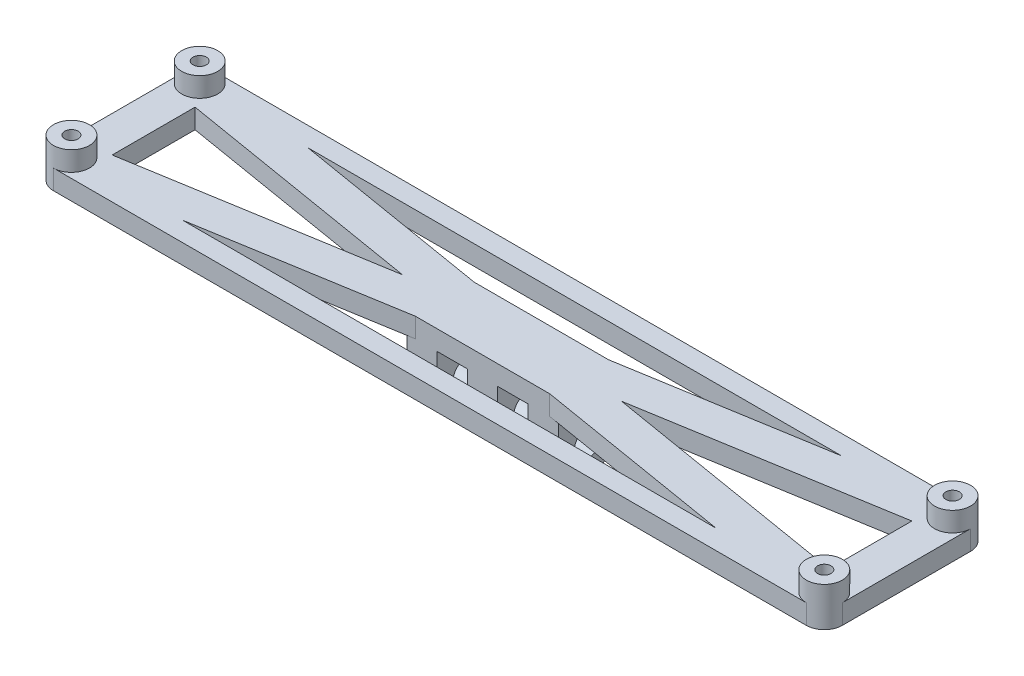
SolidWorks part; units mm, degrees
material "CARBON FIBER TEST"
ref_plane "Front Plane" through (0, 0, 0) normal (0, 0, 1) x (1, 0, 0)
ref_plane "Top Plane" through (0, 0, 0) normal (0, 1, 0) x (1, 0, 0)
ref_plane "Right Plane" through (0, 0, 0) normal (1, 0, 0) x (0, 0, -1)
sketch "Sketch1" plane through (0, 0, 0) normal (0, 1, 0) x (1, 0, 0)
  line L1 (-38.36, 6.39) -> (-27.1925, 6.39) construction
  line L2 (-38.36, 6.39) -> (-38.36, -6.39) construction
  line L3 (-38.36, -6.39) -> (-36.525, -6.39) construction
  line L4 (38.36, 4.555) -> (38.36, 4.5297) construction
  line L7 (-38.0585, 8.2001) -> (-3.0899, 2.375) construction
  line L8 (-38.6615, 4.5799) -> (-11.1675, 0) construction
  line L10 (-38.6615, -4.5799) -> (-11.1675, 0) construction
  line L12 (11.1675, 0) -> (36.525, -4.224) construction
  line L13 (-3.0899, 2.375) -> (3.0899, 2.375) construction
  line L15 (-3.0899, -2.375) -> (3.0899, -2.375) construction
  line L17 (-38.36, 6.39) -> (-38.36, -6.39) construction
  line L18 (3.0899, 2.375) -> (16.1767, 4.555) construction
  line L19 (11.1675, 0) -> (36.525, 4.224) construction
  line L24 (3.0899, -2.375) -> (16.1767, -4.555) construction
  line L25 (-36.525, 6.39) -> (-36.525, -4.555) construction
  line L26 (-40.195, 6.39) -> (-40.195, -6.39) construction
  line L30 (-38.36, -6.39) -> (-36.525, -6.39) construction
  line L31 (-38.36, -4.555) -> (-36.525, -4.555) construction
  line L32 (-38.36, -8.225) -> (38.36, -8.225) construction
  line L33 (38.36, 4.555) -> (38.36, 4.5297) construction
  line L34 (40.195, 6.39) -> (40.195, -6.39) construction
  line L35 (36.525, 4.224) -> (36.525, -4.555) construction
  line L37 (16.1767, 4.555) -> (-38.36, 4.555) construction
  line L38 (38.36, 8.225) -> (-38.36, 8.225) construction
  line L39 (38.36, -4.5297) -> (38.6615, -4.5799) construction
  line L41 (-27.1925, 6.39) -> (-38.36, 6.39) construction
  line L42 (38.36, -4.5297) -> (38.36, -6.39) construction
  line L43 (38.36, -4.5297) -> (38.36, -6.39) construction
  line L44 (-16.1767, -4.555) -> (-3.0899, -2.375) construction
  line L45 (-16.1767, -4.555) -> (16.1767, -4.555) construction
  arc A0 (-38.0585, 8.2001) -> (-38.6615, 4.5799) centre (-38.36, 6.39) ccw construction
  arc A1 (38.0585, -8.2001) -> (38.6615, -4.5799) centre (38.36, -6.39) ccw construction
  arc A2 (-38.6615, -4.5799) -> (-38.0585, -8.2001) centre (-38.36, -6.39) ccw construction
  arc A3 (40.195, 6.39) -> (38.0585, 8.2001) centre (38.36, 6.39) ccw construction
  arc A4 (-36.525, 6.39) -> (-40.195, 6.39) centre (-38.36, 6.39) ccw construction
  arc A5 (-40.195, -6.39) -> (-36.525, -6.39) centre (-38.36, -6.39) ccw construction
  arc A8 (-38.36, -4.555) -> (-38.36, -8.225) centre (-38.36, -6.39) ccw construction
  arc A9 (38.36, -8.225) -> (38.36, -4.555) centre (38.36, -6.39) ccw construction
  arc A10 (40.195, 6.39) -> (38.0585, 8.2001) centre (38.36, 6.39) ccw construction
  arc A11 (38.0585, -8.2001) -> (40.195, -6.39) centre (38.36, -6.39) ccw construction
  arc A13 (-38.36, 8.225) -> (-38.36, 4.555) centre (-38.36, 6.39) ccw construction
  arc A14 (40.195, 6.39) -> (38.36, 8.225) centre (38.36, 6.39) ccw construction
  circle A15 centre (-38.36, 6.39) radius 1.2491
  point P0 (0, 0)
  point P6 (0, 0)
  point P11 (0, 0)
  point P16 (0, 0)
  point P17 (-38.36, 0)
  point P26 (0, 6.39)
  point P35 (0, -6.39)
  point P43 (38.36, 0)
  dimension "D2" = 12.78
sketch "Sketch2" plane through (0, 0, 0) normal (0, 1, 0) x (1, 0, 0)
  line L0 (-38.36, 6.39) -> (38.36, -6.39) construction
  line L1 (38.36, -6.39) -> (-38.36, -6.39) construction
  line L2 (38.36, -6.39) -> (38.36, 6.39) construction
  line L3 (38.36, 6.39) -> (-38.36, 6.39) construction
  line L4 (-38.36, -6.39) -> (-38.36, 6.39) construction
  line L5 (38.36, -6.39) -> (-38.36, 6.39) construction
  line L6 (38.36, 6.39) -> (-38.36, -6.39) construction
  line L7 (-38.0585, 8.2001) -> (38.6615, -4.5799) construction
  line L8 (-38.6615, 4.5799) -> (38.0585, -8.2001) construction
  line L9 (-38.36, -6.39) -> (38.36, 6.39) construction
  line L10 (-38.6615, -4.5799) -> (38.0585, 8.2001) construction
  line L11 (-38.0585, -8.2001) -> (38.6615, 4.5799) construction
  line L12 (-38.36, 6.39) -> (-38.36, -6.39) construction
  line L19 (-36.525, 6.39) -> (-36.525, -6.39) construction
  line L20 (-40.195, 6.39) -> (-40.195, -6.39) construction
  line L21 (38.36, 6.39) -> (38.36, -6.39) construction
  line L22 (40.195, 6.39) -> (40.195, -6.39) construction
  line L23 (36.525, 6.39) -> (36.525, -6.39) construction
  line L24 (-38.36, 6.39) -> (38.36, 6.39) construction
  line L25 (-38.36, 8.225) -> (38.36, 8.225) construction
  line L26 (-38.36, 4.555) -> (38.36, 4.555) construction
  line L27 (-38.36, -6.39) -> (38.36, -6.39) construction
  line L28 (-38.36, -4.555) -> (38.36, -4.555) construction
  line L29 (-38.36, -8.225) -> (38.36, -8.225) construction
  line L31 (-7.715, 3) -> (7.715, 3)
  line L32 (-7.715, 3) -> (-7.715, -3)
  line L33 (-7.715, -3) -> (7.715, -3)
  line L34 (7.715, 3) -> (7.715, -3)
  line L35 (-7.715, 3) -> (7.715, -3) construction
  line L36 (-7.715, -3) -> (7.715, 3) construction
  arc A0 (-38.0585, 8.2001) -> (-38.6615, 4.5799) centre (-38.36, 6.39) ccw construction
  arc A1 (38.0585, -8.2001) -> (38.6615, -4.5799) centre (38.36, -6.39) ccw construction
  arc A2 (-38.6615, -4.5799) -> (-38.0585, -8.2001) centre (-38.36, -6.39) ccw construction
  arc A3 (38.6615, 4.5799) -> (38.0585, 8.2001) centre (38.36, 6.39) ccw construction
  arc A4 (-36.525, 6.39) -> (-40.195, 6.39) centre (-38.36, 6.39) ccw construction
  arc A5 (-40.195, -6.39) -> (-36.525, -6.39) centre (-38.36, -6.39) ccw construction
  arc A6 (40.195, 6.39) -> (36.525, 6.39) centre (38.36, 6.39) ccw construction
  arc A7 (36.525, -6.39) -> (40.195, -6.39) centre (38.36, -6.39) ccw construction
  arc A8 (-38.36, 8.225) -> (-38.36, 4.555) centre (-38.36, 6.39) ccw construction
  arc A9 (38.36, 4.555) -> (38.36, 8.225) centre (38.36, 6.39) ccw construction
  arc A10 (-38.36, -4.555) -> (-38.36, -8.225) centre (-38.36, -6.39) ccw construction
  arc A11 (38.36, -8.225) -> (38.36, -4.555) centre (38.36, -6.39) ccw construction
  point P0 (0, 0)
  point P7 (0, 0)
  point P12 (0, 0)
  point P17 (0, 0)
  point P18 (0, 0)
  point P25 (-38.36, 0)
  point P30 (38.36, 0)
  point P39 (0, 6.39)
  point P46 (0, -6.39)
  dimension "D1" = 15.43
  dimension "D2" = 6
sketch "Sketch3" plane through (0, 0, 0) normal (0, 1, 0) x (1, 0, 0)
  line L2 (6.8419, -3) -> (27.1925, -6.39)
  line L5 (-27.1925, 6.39) -> (-6.8419, 3)
  line L6 (0, 0) -> (-4.9915, 0) construction
  line L7 (-36.525, 4.224) -> (-36.525, -4.224)
  line L8 (-36.525, 6.39) -> (-36.525, -4.555) construction
  line L9 (-38.6615, 4.5799) -> (-11.1675, 0) construction
  line L10 (-38.6615, -4.5799) -> (-11.1675, 0) construction
  line L11 (-36.525, -4.224) -> (-11.1675, 0)
  line L12 (-11.1675, 0) -> (-36.525, 4.224)
  line L13 (6.8419, 3) -> (27.1925, 6.39)
  line L14 (38.36, 6.39) -> (-38.36, 6.39) construction
  line L15 (-38.6615, -4.5799) -> (38.0585, 8.2001) construction
  line L16 (27.1925, 6.39) -> (-27.1925, 6.39)
  line L17 (0, 0) -> (32.5589, 0) construction
  line L18 (-6.8419, -3) -> (6.8419, -3)
  line L19 (0, 0) -> (0, -14.67) construction
  line L20 (-27.1925, -6.39) -> (-6.8419, -3)
  line L21 (27.1925, -6.39) -> (-27.1925, -6.39)
  line L22 (36.525, -4.224) -> (11.1675, 0)
  line L23 (36.525, 4.224) -> (36.525, -4.224)
  line L24 (11.1675, 0) -> (36.525, 4.224)
  line L25 (-6.8419, 3) -> (6.8419, 3)
  line L26 (38.36, -8.37) -> (-38.36, -8.37)
  line L27 (40.195, -6.535) -> (40.195, 6.535)
  line L28 (38.36, 8.37) -> (-38.36, 8.37)
  line L29 (-40.195, -6.535) -> (-40.195, 6.535)
  line L30 (40.195, -8.37) -> (-40.195, 8.37) construction
  line L31 (40.195, 8.37) -> (-40.195, -8.37) construction
  arc A0 (-40.195, 6.535) -> (-38.36, 8.37) centre (-38.36, 6.535) cw
  arc A1 (38.36, -8.37) -> (40.195, -6.535) centre (38.36, -6.535) ccw
  arc A2 (40.195, 6.535) -> (38.36, 8.37) centre (38.36, 6.535) ccw
  arc A3 (-38.36, -8.37) -> (-40.195, -6.535) centre (-38.36, -6.535) cw
  dimension "D3" = 1.835
  dimension "D4" = 1.835
  dimension "D1" = 16.74
  dimension "D2" = 80.39
  dimension "D5" = 6
extrude "Boss-Extrude2" add sketch "Sketch3" along normal blind 2
ref_plane "Plane2" through (7.715, 0, 0) normal (-1, 0, 0) x (0, 0, 1)
sketch "Sketch7" plane through (7.715, 0, 0) normal (-1, 0, 0) x (0, 0, 1)
  line L0 (-3, 0) -> (3, 0) construction
  line L4 (-3, 0) -> (3, 0)
  line L5 (-3, -3.4) -> (-3, 0)
  line L6 (3, -3.4) -> (3, 0)
  circle A2 centre (0, -3.4) radius 1.375
  arc A3 (-3, -3.4) -> (3, -3.4) centre (0, -3.4) ccw
  dimension "D1" = 2.75
  dimension "D3" = 3.4
  dimension "D2" = 6
extrude "Boss-Extrude4" add sketch "Sketch7" along normal blind 3.086
pattern_linear "LPattern1" count 3 spacing 6.172 along (-1, 0, 0) of "Boss-Extrude4"
sketch "Sketch8" plane through (0, 2, 0) normal (0, 1, 0) x (1, 0, 0)
  line L0 (-40.195, 4.7227) -> (-38.36, 4.7227) construction
  line L1 (-40.195, 6.535) -> (-40.195, -6.535) construction
  line L2 (-36.6331, 8.37) -> (-36.6331, 6.535) construction
  line L3 (38.36, 8.37) -> (-38.36, 8.37) construction
  line L4 (0, 0) -> (0, -4.7834) construction
  circle A0 centre (-38.36, 6.535) radius 0.985 construction
  circle A1 centre (38.36, 6.535) radius 0.985 construction
  circle A2 centre (-38.36, 6.535) radius 1.835
  arc A4 (-38.36, 8.37) -> (-40.195, 6.535) centre (-38.36, 6.535) ccw construction
  point P4 (-37.375, 6.535)
  point P5 (-39.345, 6.535)
  point P6 (37.375, 6.535)
  point P7 (39.345, 6.535)
  dimension "D1" = 74.75
  dimension "D2" = 78.69
extrude "Boss-Extrude5" add sketch "Sketch8" along normal blind 2
sketch "Sketch9" plane through (0, 4, 0) normal (0, 1, 0) x (1, 0, 0)
  circle A0 centre (-38.36, 6.535) radius 0.685
  point P3 (-37.675, 6.535)
  dimension "D1" = 0.3
extrude "Cut-Extrude1" cut sketch "Sketch9" against normal through all
mirror "Mirror1" about plane through (0, 0, 0) normal (1, 0, 0) of "Boss-Extrude5", "Cut-Extrude1" second plane through (0, 0, 0) second plane normal (0, 0, 1)
